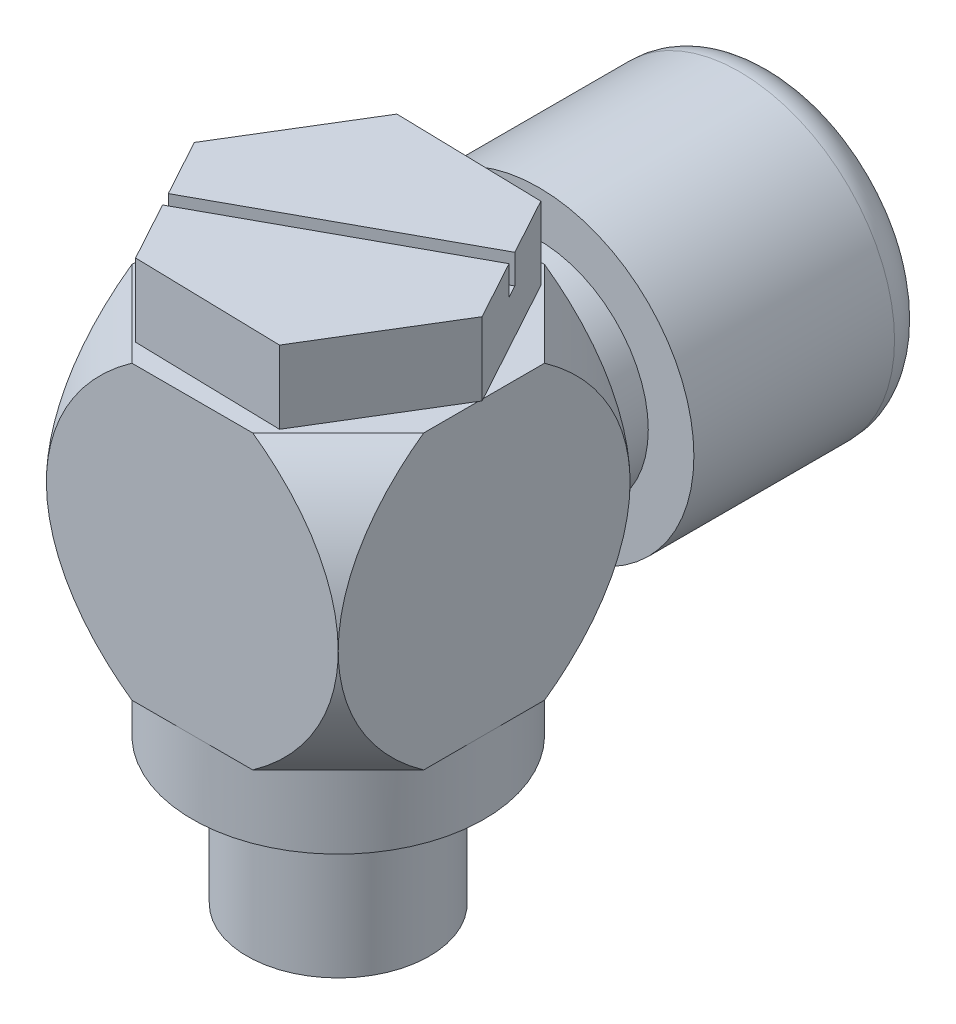
SolidWorks part; units mm, degrees
ref_plane "Plan de face" through (0, 0, 0) normal (0, 0, 1) x (1, 0, 0)
ref_plane "Plan de dessus" through (0, 0, 0) normal (0, 1, 0) x (1, 0, 0)
ref_plane "Plan de droite" through (0, 0, 0) normal (1, 0, 0) x (0, 0, -1)
sketch "Esquisse1" plane through (0, 0, 0) normal (0, 0, 1) x (1, 0, 0)
  line L1 (-8.6276, -5.4391) -> (-0.6276, -5.4391)
  line L2 (-8.6276, -5.4391) -> (-8.6276, -13.4391)
  line L3 (-8.6276, -13.4391) -> (-0.6276, -13.4391)
  line L4 (-0.6276, -5.4391) -> (-0.6276, -13.4391)
  dimension "D1" = 8
  dimension "D2" = 8
extrude "Extrusion1" add sketch "Esquisse1" along normal blind 8
ref_plane "Plan1" through (-4.3138, 0, 4.3138) normal (0.7071, 0, -0.7071) x (-0.7071, 0, -0.7071)
sketch "Esquisse2" plane through (-4.3138, 0, 4.3138) normal (0.7071, 0, -0.7071) x (-0.7071, 0, -0.7071)
  line L0 (0.4437, -13.4391) -> (0.4437, -5.4391) construction
  circle A0 centre (0.4437, -9.4391) radius 5.6569
  circle A1 centre (0.4437, -9.4391) radius 7.8644
extrude "Enlèv. mat.-Extru.1" cut sketch "Esquisse2" against normal mid plane 18
ref_plane "Plan2" through (-0.3138, 0, -0.3138) normal (0.7071, 0, 0.7071) x (0.7071, 0, -0.7071)
sketch "Esquisse3" plane through (-0.3138, 0, -0.3138) normal (0.7071, 0, 0.7071) x (0.7071, 0, -0.7071)
  circle A0 centre (-6.1006, -9.4391) radius 5.6569
  circle A1 centre (-6.1006, -9.4391) radius 8.3522
extrude "Enlèv. mat.-Extru.2" cut sketch "Esquisse3" against normal mid plane 18
sketch "Esquisse4" plane through (0, -5.4391, 0) normal (0, 1, 0) x (-1, 0, 0)
  line L0 (-0.28, 8.9075) -> (8.9075, -0.28) construction
  line L1 (2.6902, 7.5469) -> (0.5872, 4.0957)
  line L2 (0.5872, 4.0957) -> (2.5245, 0.5488)
  line L3 (2.5245, 0.5488) -> (6.5649, 0.4531)
  line L4 (6.5649, 0.4531) -> (8.6679, 3.9043)
  line L5 (8.6679, 3.9043) -> (6.7306, 7.4512)
  line L6 (6.7306, 7.4512) -> (2.6902, 7.5469)
  circle A0 centre (4.6276, 4) radius 3.5 construction
extrude "Extrusion2" add sketch "Esquisse4" along normal blind 2
sketch "Esquisse5" plane through (0, -13.4391, 0) normal (0, -1, 0) x (1, 0, 0)
  line L0 (-7.425, 1.2025) -> (-1.2025, 7.425) construction
  circle A0 centre (-4.6276, 4) radius 4
extrude "Extrusion3" add sketch "Esquisse5" along normal blind 2
sketch "Esquisse6" plane through (0, -15.4391, 0) normal (0, -1, 0) x (1, 0, 0)
  circle A0 centre (-4.6276, 4) radius 2.5
extrude "Extrusion4" add sketch "Esquisse6" along normal blind 4
sketch "Esquisse7" plane through (0, 0, 0) normal (0, 0, -1) x (-1, 0, 0)
  circle A0 centre (4.6276, -9.4391) radius 3
extrude "Extrusion5" add sketch "Esquisse7" along normal blind 1.5
sketch "Esquisse8" plane through (0, 0, -1.5) normal (0, 0, -1) x (-1, 0, 0)
  circle A0 centre (4.6276, -9.4391) radius 4.25
extrude "Extrusion6" add sketch "Esquisse8" along normal blind 6.5
fillet "Congé1" radius 1 1 edges at (-8.8776, -9.4391, -8)
sketch "Esquisse9" plane through (0, -3.4391, 0) normal (0, 1, 0) x (-1, 0, 0)
  line L0 (1.3219, 1.93) -> (8.1516, 5.6604)
  line L1 (1.3219, 1.93) -> (1.131, 2.2796)
  line L2 (8.1516, 5.6604) -> (7.9606, 6.0101)
  line L3 (1.131, 2.2796) -> (7.9606, 6.0101)
extrude "Enlèv. mat.-Extru.3" cut sketch "Esquisse9" against normal blind 0.8
